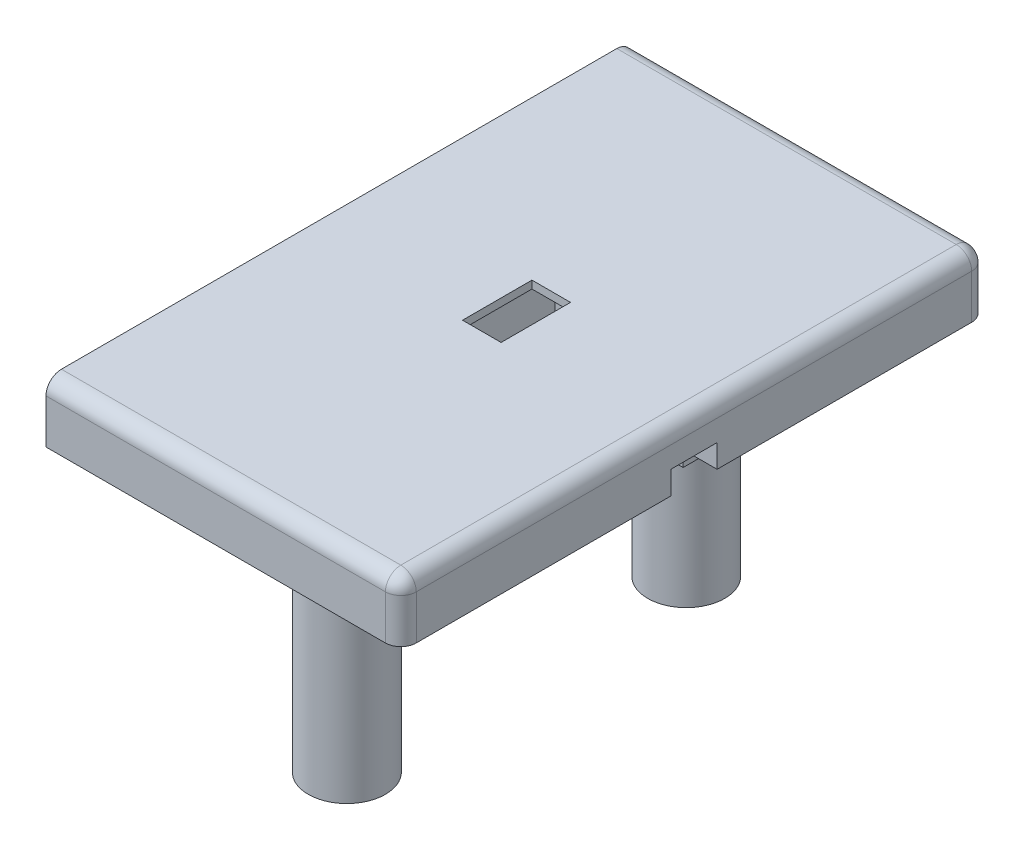
SolidWorks part; units mm, degrees
ref_plane "Front" through (0, 0, 0) normal (0, 0, 1) x (1, 0, 0)
ref_plane "Top" through (0, 0, 0) normal (0, 1, 0) x (1, 0, 0)
ref_plane "Right" through (0, 0, 0) normal (1, 0, 0) x (0, 0, -1)
sketch "Sketch1" plane through (0, 0, 0) normal (0, 1, 0) x (1, 0, 0)
  line L1 (-11.5, 19) -> (11.5, 19)
  line L2 (-11.5, 19) -> (-11.5, -19)
  line L3 (-11.5, -19) -> (11.5, -19)
  line L4 (11.5, 19) -> (11.5, -19)
  line L5 (-11.5, 19) -> (11.5, -19) construction
  line L6 (-11.5, -19) -> (11.5, 19) construction
  point P0 (0, 0)
  dimension "D1" = 38
  dimension "D2" = 23
extrude "Boss-Extrude1" add sketch "Sketch1" along normal blind 4.87
fillet "Fillet1" radius 1 5 edges at (11.5, 2.435, -19) (11.5, 2.435, 19) (0, 4.87, 19) (11.5, 4.87, 0) (0, 4.87, -19)
sketch "Sketch2" plane through (0, 0, 0) normal (0, -1, 0) x (1, 0, 0)
  line L1 (11.5, -19) -> (-11.5, -19)
  line L2 (11.5, -19) -> (11.5, 19)
  line L3 (11.5, 19) -> (-11.5, 19)
  line L4 (-11.5, -19) -> (-11.5, 19)
  line L5 (11.5, -19) -> (-11.5, 19) construction
  line L6 (11.5, 19) -> (-11.5, -19) construction
  line L7 (9.3, -16.8) -> (-9.3, -16.8)
  line L8 (9.3, -16.8) -> (9.3, 16.8)
  line L9 (9.3, 16.8) -> (-9.3, 16.8)
  line L10 (-9.3, -16.8) -> (-9.3, 16.8)
  line L11 (9.3, -16.8) -> (-9.3, 16.8) construction
  line L12 (9.3, 16.8) -> (-9.3, -16.8) construction
  point P0 (0, 0)
  point P7 (0, 0)
  dimension "D1" = 2.2
  dimension "D2" = 2.2
extrude "Cut-Extrude1" cut sketch "Sketch2" against normal blind 1
sketch "Sketch3" plane through (0, 0, 0) normal (0, -1, 0) x (1, 0, 0)
  line L1 (2.5, -5) -> (-2.5, -5)
  line L2 (2.5, -5) -> (2.5, 5)
  line L3 (2.5, 5) -> (-2.5, 5)
  line L4 (-2.5, -5) -> (-2.5, 5)
  line L5 (2.5, -5) -> (-2.5, 5) construction
  line L6 (2.5, 5) -> (-2.5, -5) construction
  point P0 (0, 0)
  dimension "D1" = 10
  dimension "D2" = 5
extrude "Cut-Extrude2" cut sketch "Sketch3" against normal offset from surface (4.37 mm away) 0.5 up to face at (-0.5, 4.87, 0)
sketch "Sketch4" plane through (0, 4.37, 0) normal (0, -1, 0) x (1, 0, 0)
  line L1 (1.25, -2.25) -> (-1.25, -2.25)
  line L2 (1.25, -2.25) -> (1.25, 2.25)
  line L3 (1.25, 2.25) -> (-1.25, 2.25)
  line L4 (-1.25, -2.25) -> (-1.25, 2.25)
  line L5 (1.25, -2.25) -> (-1.25, 2.25) construction
  line L6 (1.25, 2.25) -> (-1.25, -2.25) construction
  point P0 (0, 0)
  dimension "D1" = 2.5
  dimension "D2" = 4.5
extrude "Cut-Extrude3" cut sketch "Sketch4" against normal up to next
sketch "Sketch5" plane through (0, 0, 0) normal (0, -1, 0) x (1, 0, 0)
  line L0 (2.5, 5) -> (-2.5, 5) construction
  line L4 (-11.5, -19) -> (10.5, -19) construction
  line L5 (10.5, 19) -> (-11.5, 19) construction
  circle A0 centre (0, -11) radius 2.5
  circle A1 centre (0, 11) radius 2.5
  point P7 (0, 5)
  dimension "D1" = 5
  dimension "D2" = 5
  dimension "D3" = 8
  dimension "D4" = 8
extrude "Boss-Extrude2" add sketch "Sketch5" along normal blind 15.5
sketch "Sketch6" plane through (0, -15.5, 0) normal (0, -1, 0) x (1, 0, 0)
  circle A0 centre (0, -11) radius 0.95
  circle A1 centre (0, 11) radius 0.95
  dimension "D1" = 1.9
  dimension "D2" = 1.9
extrude "Cut-Extrude4" cut sketch "Sketch6" against normal blind 6
sketch "Sketch7" plane through (11.5, 0, 0) normal (1, 0, 0) x (0, 0, -1)
  line L0 (18, 1) -> (-18, 1) construction
  line L1 (1.5, 2.5) -> (-1.5, 2.5)
  line L2 (1.5, 2.5) -> (1.5, -2.5)
  line L3 (1.5, -2.5) -> (-1.5, -2.5)
  line L4 (-1.5, 2.5) -> (-1.5, -2.5)
  line L5 (1.5, 2.5) -> (-1.5, -2.5) construction
  line L6 (1.5, -2.5) -> (-1.5, 2.5) construction
  point P0 (0, 0)
  dimension "D1" = 3
  dimension "D2" = 1.5
extrude "Cut-Extrude5" cut sketch "Sketch7" against normal offset from surface (4.2 mm away) 2 up to face at (9.3, 0.5, 0) offset beyond the face yes
equation "\"D2@Sketch2\"=\"D1@Sketch2\""
equation "\"D2@Sketch5\"=\"D1@Sketch5\""
equation "\"D4@Sketch5\"=\"D3@Sketch5\""
